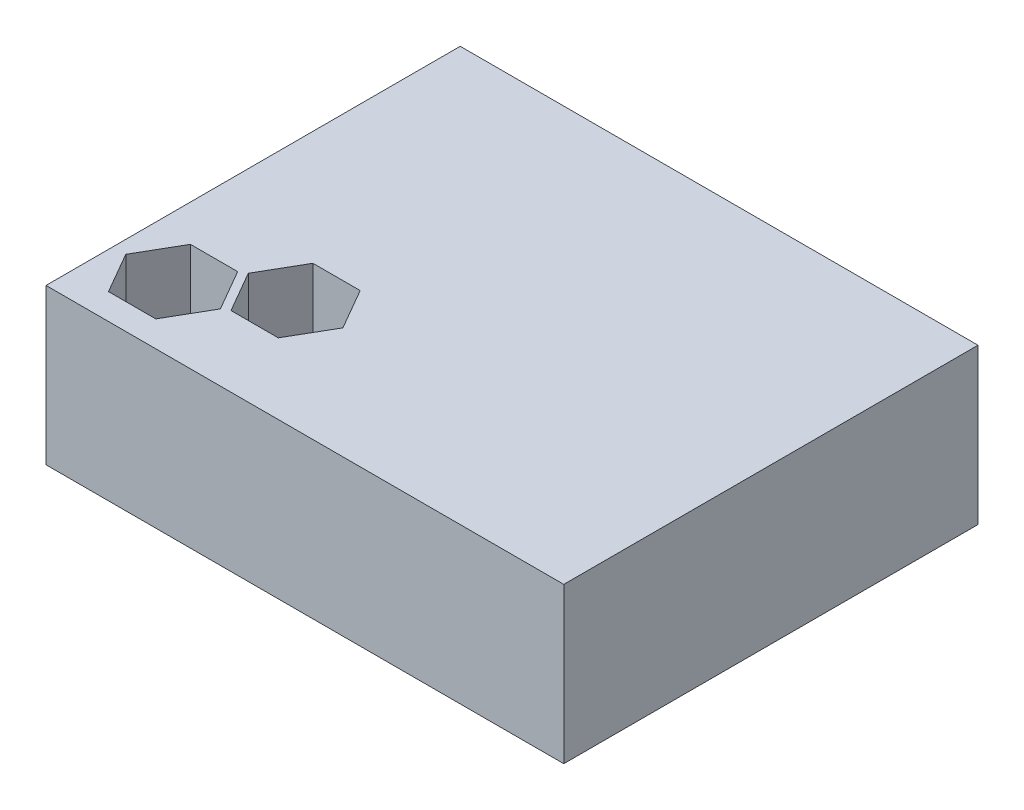
SolidWorks part; units mm, degrees
material "AISI 1020"
ref_plane "Front Plane" through (0, 0, 0) normal (0, 0, 1) x (1, 0, 0)
ref_plane "Top Plane" through (0, 0, 0) normal (0, 1, 0) x (1, 0, 0)
ref_plane "Right Plane" through (0, 0, 0) normal (1, 0, 0) x (0, 0, -1)
sketch "Sketch1" plane through (0, 0, 0) normal (0, 1, 0) x (1, 0, 0)
  line L1 (0, 0) -> (10, 0)
  line L2 (0, 0) -> (0, 8)
  line L3 (0, 8) -> (10, 8)
  line L4 (10, 0) -> (10, 8)
  dimension "D1" = 10
  dimension "D2" = 8
extrude "Boss-Extrude1" add sketch "Sketch1" along normal blind 3
sketch "Sketch2" plane through (0, 3, 0) normal (0, 1, 0) x (1, 0, 0)
  line L0 (1.1634, 1.291) -> (2.6634, 2.1571) construction
  line L1 (2.0768, 1.291) -> (1.6201, 2.0821)
  line L2 (1.6201, 2.0821) -> (0.7067, 2.0821)
  line L3 (0.7067, 2.0821) -> (0.25, 1.291)
  line L4 (0.25, 1.291) -> (0.7067, 0.5)
  line L5 (0.7067, 0.5) -> (1.6201, 0.5)
  line L6 (1.6201, 0.5) -> (2.0768, 1.291)
  line L7 (3.5768, 2.1571) -> (3.1201, 2.9481)
  line L8 (3.1201, 2.9481) -> (2.2067, 2.9481)
  line L9 (2.2067, 2.9481) -> (1.75, 2.1571)
  line L10 (1.75, 2.1571) -> (2.2067, 1.366)
  line L11 (2.2067, 1.366) -> (3.1201, 1.366)
  line L12 (3.1201, 1.366) -> (3.5768, 2.1571)
  line L13 (0, 0) -> (10, 0) construction
  line L14 (0, 8) -> (0, 0) construction
  line L15 (2.6634, 2.1571) -> (4.1634, 1.291) construction
  line L16 (4.1634, 1.291) -> (1.1634, 1.291) construction
  line L17 (1.1634, 2.0821) -> (1.1634, 2.2321) construction
  line L18 (1.1634, 2.2321) -> (1.1634, 3.0231) construction
  line L19 (1.1634, 2.0821) -> (1.1634, 1.291) construction
  line L20 (2.0768, 1.291) -> (2.2067, 1.366) construction
  circle A0 centre (1.1634, 1.291) radius 0.791 construction
  circle A1 centre (2.6634, 2.1571) radius 0.791 construction
  dimension "D1" = 0.5
  dimension "D2" = 0.25
  dimension "D3" = 0.15
  dimension "D4" = 30
  dimension "D5" = 3
  dimension "D6" = 1.7321
extrude "Cut-Extrude1" cut sketch "Sketch2" against normal up to next
